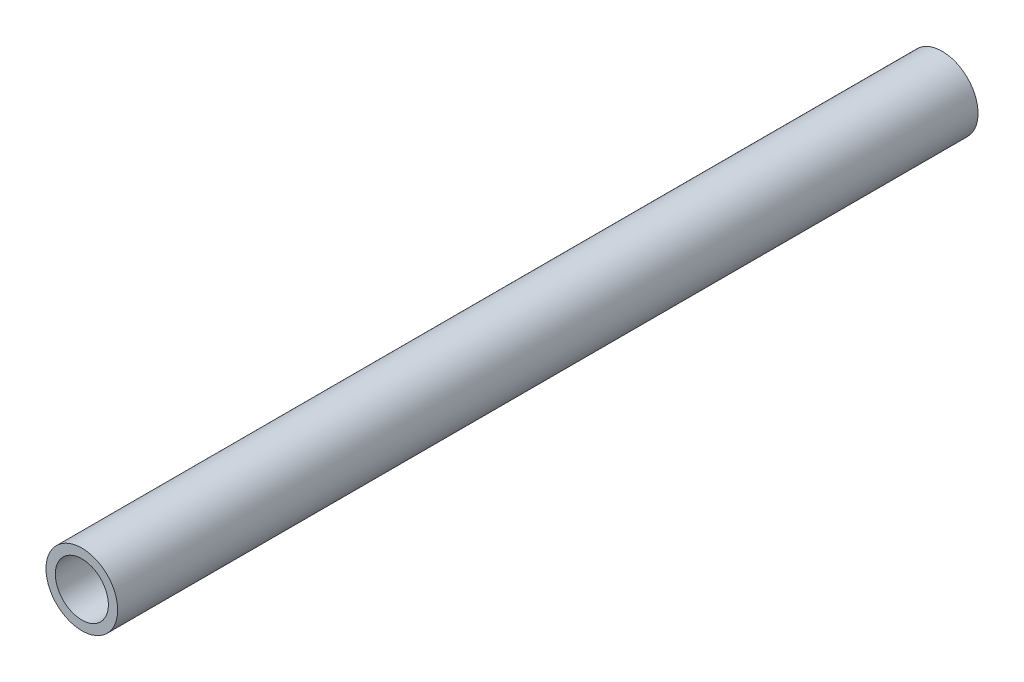
SolidWorks part; units mm, degrees
ref_plane "Front Plane" through (0, 0, 0) normal (0, 0, 1) x (1, 0, 0)
ref_plane "Top Plane" through (0, 0, 0) normal (0, 1, 0) x (1, 0, 0)
ref_plane "Right Plane" through (0, 0, 0) normal (1, 0, 0) x (0, 0, -1)
sketch "Sketch1" plane through (0, 0, 0) normal (0, 0, 1) x (1, 0, 0)
  line L0 (-6.35, 0) -> (0, 0) construction
  circle A0 centre (0, 0) radius 6.35
  circle A1 centre (0, 0) radius 4.699
  point P5 (-4.699, 0)
  point P6 (-6.35, 0)
  dimension "ID" = 9.398
  dimension "OD" = 12.7
  dimension "Wall Thickness" = 1.651
sketch "Sketch2" plane through (0, 0, 0) normal (1, 0, 0) x (0, 0, -1)
  line L0 (-76.2, 0) -> (76.2, 0) construction
  line L1 (0, 6.35) -> (0, -6.35) construction
  line L2 (0, 6.35) -> (0, -6.35) construction
  point P4 (0, 0)
  point P7 (60.325, 0)
  point P8 (-60.325, 0)
  dimension "D1" = 15.875
  dimension "Length" = 152.4
sketch "Sketch3" plane through (0, 0, 0) normal (0, 0, 1) x (1, 0, 0)
  circle A1 centre (0, 0) radius 4.699
  circle A2 centre (0, 0) radius 4.699
  circle A3 centre (0, 0) radius 6.35
  circle A4 centre (0, 0) radius 6.35
  dimension "D1" = 0
  dimension "D2" = 0
extrude "Boss-Extrude1" add sketch "Sketch3" along normal mid plane 152.4
equation "\"D1@Sketch2\"=\"OD@Sketch1\"*1.25"
equation "\"D1@Boss-Extrude1\"=\"Length@Sketch2\""
